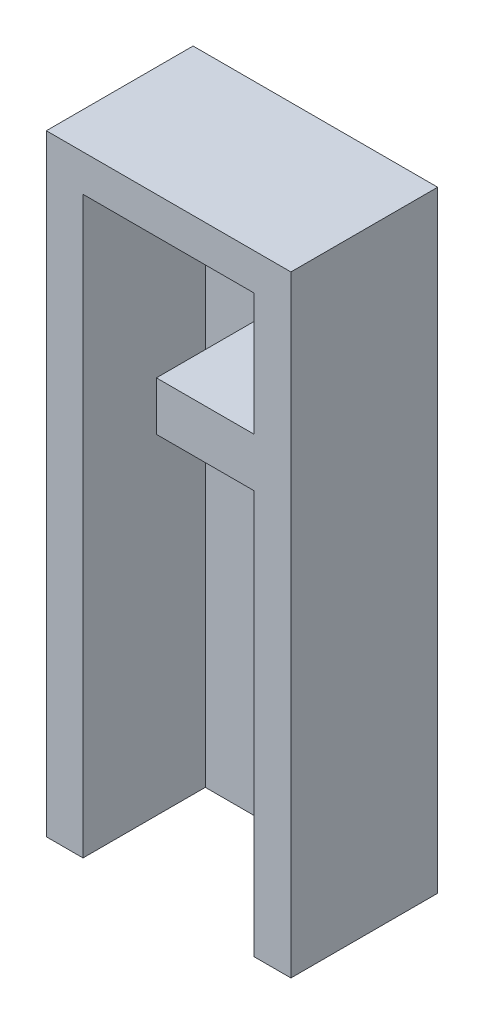
SolidWorks part; units mm, degrees
ref_plane "Front Plane" through (0, 0, 0) normal (0, 0, 1) x (1, 0, 0)
ref_plane "Top Plane" through (0, 0, 0) normal (0, 1, 0) x (1, 0, 0)
ref_plane "Right Plane" through (0, 0, 0) normal (1, 0, 0) x (0, 0, -1)
sketch "Sketch1" plane through (0, 0, 0) normal (0, 0, 1) x (1, 0, 0)
  line L5 (7, 17) -> (3, 17)
  line L6 (0, 0) -> (7, 0)
  line L7 (0, 0) -> (0, 22)
  line L8 (0, 22) -> (7, 22)
  line L9 (7, 0) -> (7, 15)
  line L10 (3, 17) -> (3, 15)
  line L11 (3, 15) -> (7, 15)
  line L12 (-1.5, 23.5) -> (8.5, 23.5)
  line L13 (8.5, -1.5) -> (8.5, 23.5)
  line L14 (-1.5, -1.5) -> (8.5, -1.5)
  line L15 (-1.5, -1.5) -> (-1.5, 23.5)
  line L16 (7, 17) -> (7, 22)
  line L17 (7, 0) -> (7, 22) construction
  dimension "D1" = 7
  dimension "D2" = 4
  dimension "D3" = 2
  dimension "D4" = 15
  dimension "D5" = 5
  dimension "D6" = 1.5
extrude "Boss-Extrude1" add sketch "Sketch1" along normal blind 5
sketch "Sketch2" plane through (0, 0, 0) normal (0, 0, -1) x (-1, 0, 0)
  line L1 (-8.5, 23.5) -> (1.5, 23.5)
  line L2 (-8.5, 23.5) -> (-8.5, -1.5)
  line L3 (-8.5, -1.5) -> (1.5, -1.5)
  line L4 (1.5, 23.5) -> (1.5, -1.5)
extrude "Boss-Extrude2" add sketch "Sketch2" along normal blind 1
sketch "Sketch3" plane through (0, 0, 0) normal (0, 1, 0) x (1, 0, 0)
  line L1 (0, 0) -> (7, 0)
  line L2 (0, 0) -> (0, -5)
  line L3 (0, -5) -> (7, -5)
  line L4 (7, 0) -> (7, -5)
extrude "Cut-Extrude1" cut sketch "Sketch3" against normal blind 5
